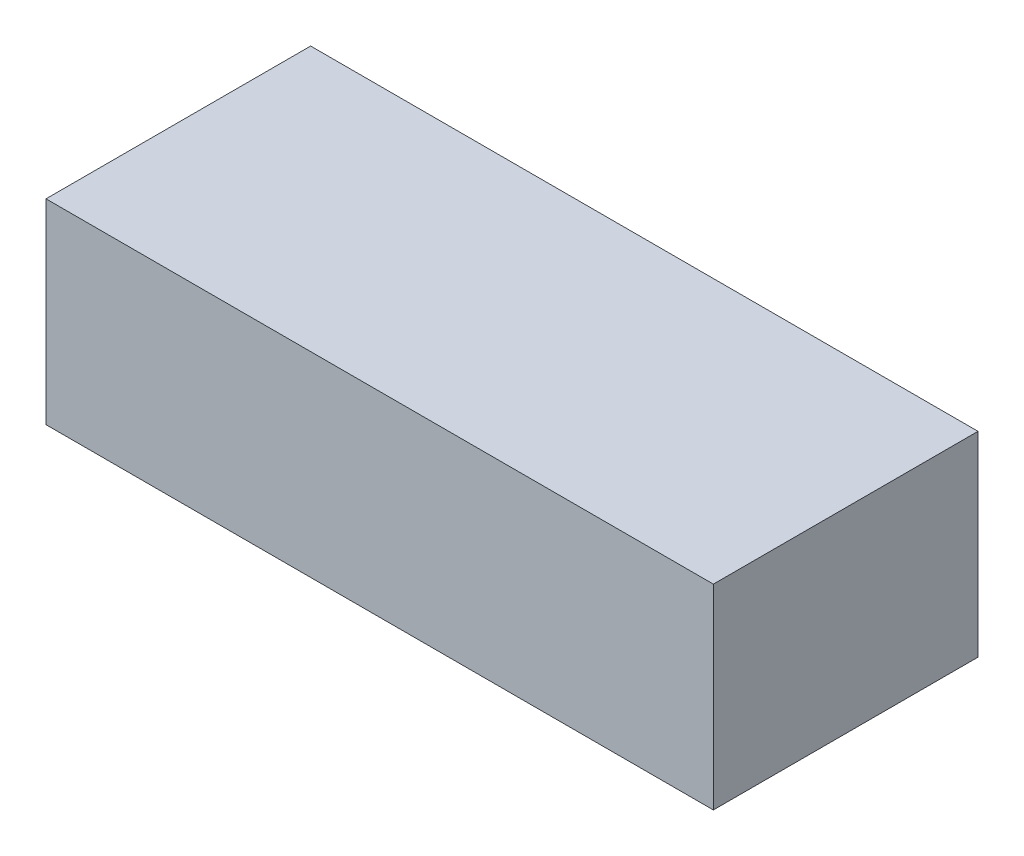
SolidWorks part; units mm, degrees
ref_plane "Alzado" through (0, 0, 0) normal (0, 0, 1) x (1, 0, 0)
ref_plane "Planta" through (0, 0, 0) normal (0, 1, 0) x (1, 0, 0)
ref_plane "Vista lateral" through (0, 0, 0) normal (1, 0, 0) x (0, 0, -1)
sketch "Croquis1" plane through (0, 0, 0) normal (0, 0, 1) x (1, 0, 0)
  line L1 (0, 0) -> (58, 0)
  line L2 (0, 0) -> (0, 17)
  line L3 (0, 17) -> (58, 17)
  line L4 (58, 0) -> (58, 17)
  dimension "D1" = 58
  dimension "D2" = 17
extrude "Saliente-Extruir1" add sketch "Croquis1" against normal blind 23
